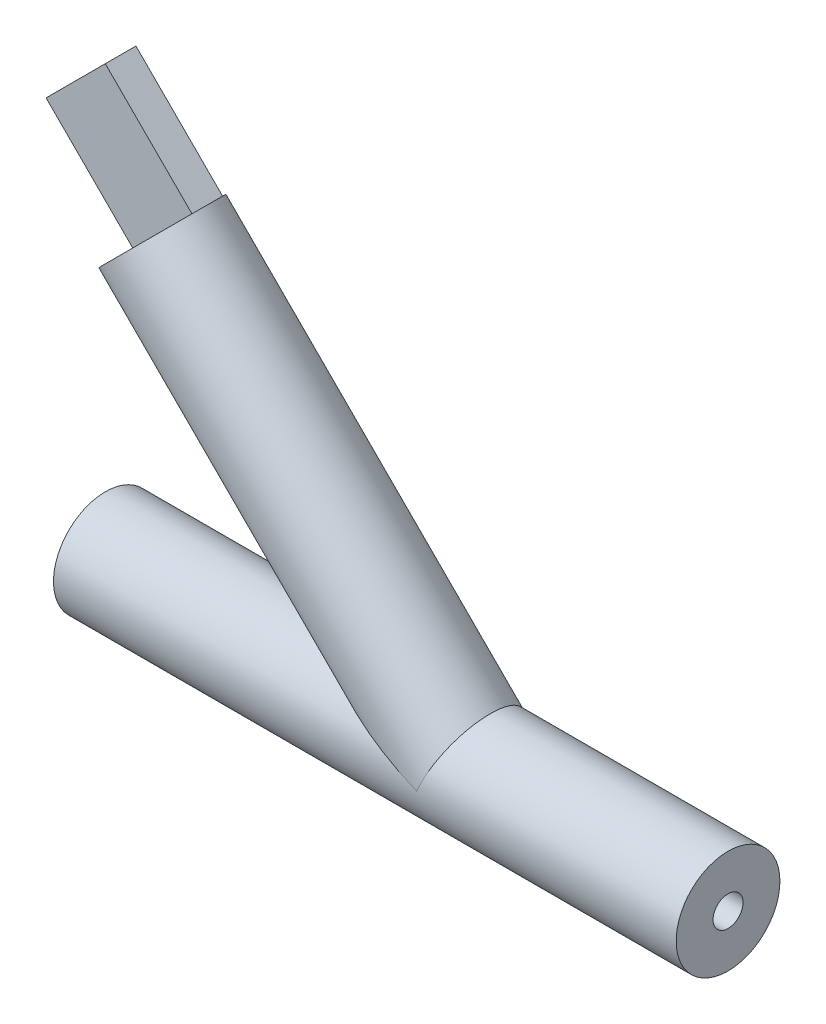
SolidWorks part; units mm, degrees
ref_plane "Front Plane" through (0, 0, 0) normal (0, 0, 1) x (1, 0, 0)
ref_plane "Top Plane" through (0, 0, 0) normal (0, 1, 0) x (1, 0, 0)
ref_plane "Right Plane" through (0, 0, 0) normal (1, 0, 0) x (0, 0, -1)
sketch "Sketch1" plane through (0, 0, 0) normal (1, 0, 0) x (0, 0, -1)
  circle A0 centre (0, 0) radius 12.7
  dimension "D1" = 25.4
extrude "Boss-Extrude1" add sketch "Sketch1" along normal blind 152.4 contours A0
sketch "Sketch4" plane through (0, 0, 0) normal (0, 1, 0) x (1, 0, 0)
  line L0 (88.9, -73.5137) -> (88.9, 26.4863)
  line L1 (152.4, -12.7) -> (152.4, 12.7) construction
  dimension "D1" = 63.5
ref_plane "Plane1" through (44.45, -44.45, 0) normal (-0.7071, 0.7071, 0) x (0.7071, 0.7071, 0)
sketch "Sketch6" plane through (0, 0, 0) normal (0, 1, 0) x (1, 0, 0)
  line L1 (152.4, -12.7) -> (152.4, 12.7) construction
  circle A0 centre (88.9, 0) radius 20
  dimension "D1" = 63.5
  dimension "D2" = 0
sketch "Sketch7" plane through (44.45, -44.45, 0) normal (-0.7071, 0.7071, 0) x (0.7071, 0.7071, 0)
  circle A0 centre (62.8618, 0) radius 12.7
  dimension "D1" = 25.4
extrude "Boss-Extrude3" add sketch "Sketch7" along normal blind 106 contours A0
sketch "Sketch10" plane through (-30.5033, 30.5033, 0) normal (-0.7071, 0.7071, 0) x (0, 0, 1)
  line L1 (-7.5, 73.1107) -> (7.5, 73.1107)
  line L2 (-7.5, 73.1107) -> (-7.5, 52.6129)
  line L3 (-7.5, 52.6129) -> (7.5, 52.6129)
  line L4 (7.5, 73.1107) -> (7.5, 52.6129)
  line L5 (-7.5, 73.1107) -> (7.5, 52.6129) construction
  line L6 (-7.5, 52.6129) -> (7.5, 73.1107) construction
  line L7 (-7.5, 73.1107) -> (0, 73.1107)
  line L8 (-7.5, 73.1107) -> (-7.5, 52.6129)
  line L9 (-7.5, 52.6129) -> (0, 52.6129)
  line L10 (0, 73.1107) -> (0, 52.6129)
  circle A0 centre (0, 62.8618) radius 12.7 construction
  point P0 (0, 62.8618)
  dimension "D1" = 15
extrude "Boss-Extrude8" add sketch "Sketch10" along normal blind 30 contours L10 L1 L2 L3
sketch "Sketch11" plane through (152.4, 0, 0) normal (1, 0, 0) x (0, 0, -1)
  circle A0 centre (0, 0) radius 3.675
  dimension "D1" = 7.35
extrude "Cut-Extrude2" cut sketch "Sketch11" against normal blind 152.4
